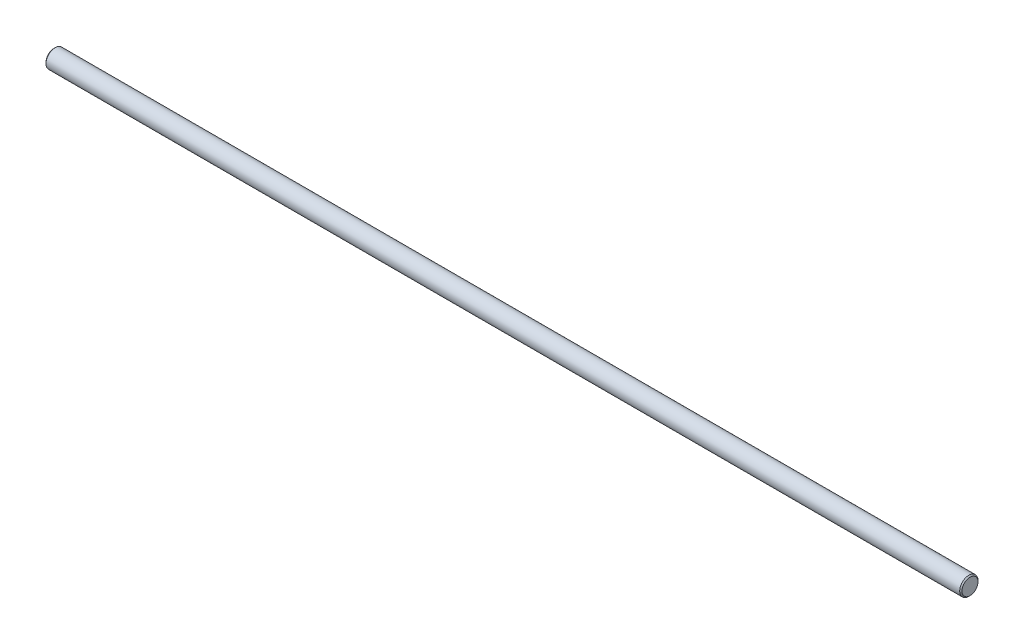
SolidWorks part; units mm, degrees
ref_plane "Front Plane" through (0, 0, 0) normal (0, 0, 1) x (1, 0, 0)
ref_plane "Top Plane" through (0, 0, 0) normal (0, 1, 0) x (1, 0, 0)
ref_plane "Right Plane" through (0, 0, 0) normal (1, 0, 0) x (0, 0, -1)
sketch "Sketch1" plane through (0, 0, 0) normal (1, 0, 0) x (0, 0, -1)
  circle A0 centre (0, 0) radius 4
  dimension "D1" = 8
extrude "Extrude1" add sketch "Sketch1" along normal blind 400
chamfer "Chamfer1" distance 0.5 angle 45 2 edges at (400, 0, -4) (0, 0, -4)
